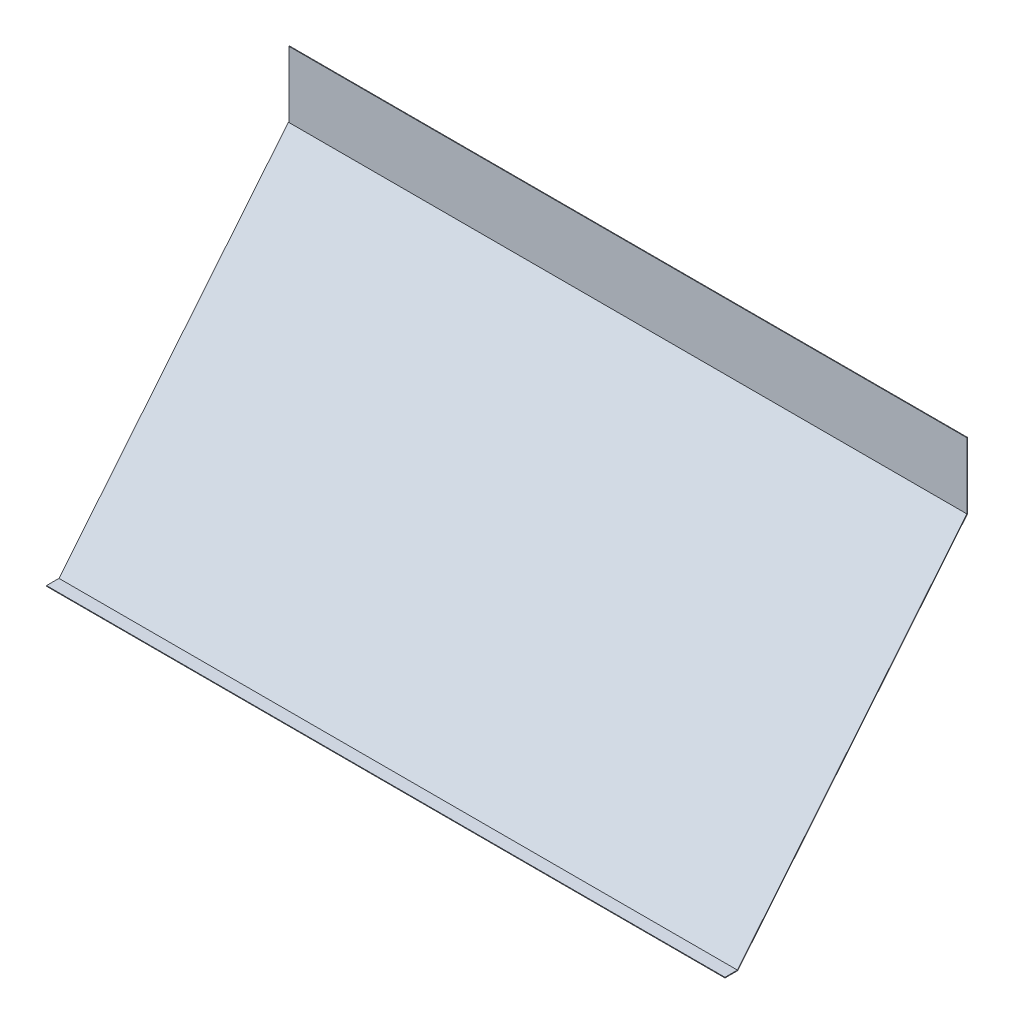
SolidWorks part; units mm, degrees
ref_plane "Front Plane" through (0, 0, 0) normal (0, 0, 1) x (1, 0, 0)
ref_plane "Top Plane" through (0, 0, 0) normal (0, 1, 0) x (1, 0, 0)
ref_plane "Right Plane" through (0, 0, 0) normal (1, 0, 0) x (0, 0, -1)
sketch "Sketch1" plane through (0, 0, 0) normal (0, 1, 0) x (1, 0, 0)
  line L1 (-545, 10) -> (545, 10)
  line L2 (-545, 10) -> (-545, -10)
  line L3 (-545, -10) -> (545, -10)
  line L4 (545, 10) -> (545, -10)
  line L5 (-545, 10) -> (545, -10) construction
  line L6 (-545, -10) -> (545, 10) construction
  point P0 (0, 0)
  dimension "D1" = 1090
  dimension "D2" = 20
extrude "Boss-Extrude1" add sketch "Sketch1" along normal blind 1
sketch "Sketch4" plane through (-545, 0, 0) normal (-1, 0, 0) x (0, 0, 1)
  line L0 (-10, 0) -> (-10, 1)
  line L1 (-10, 1) -> (-10.7738, 0.3666)
  arc A0 (-10.7738, 0.3666) -> (-10, 0) centre (-10, 1) ccw
  line M6 (-10, 1) -> (-10, 0)
  dimension "D1" = 1
  dimension "D2" = 50.7
extrude "Boss-Extrude4" add sketch "Sketch4" along direction (-1, 0, 0) on the side against the normal blind 1090 contours L1 A0 M6
sketch "Sketch5" plane through (0, 5.5002, -4.5018) normal (0, 0.7738, -0.6334) x (1, 0, 0)
  line L1 (-545, 7.105) -> (545, 7.105)
  line L2 (-545, 7.105) -> (-545, 8.105)
  line L3 (-545, 8.105) -> (545, 8.105)
  line L4 (545, 7.105) -> (545, 8.105)
extrude "Boss-Extrude5" add sketch "Sketch5" along normal blind 582
sketch "Sketch6" plane through (545, 0, 0) normal (1, 0, 0) x (0, 0, -1)
  line L0 (378.6277, 451.375) -> (379.6277, 451.375)
  line L1 (378.6277, 451.375) -> (379.4015, 450.7416) construction
  line L2 (379.4015, 450.7416) -> (378.6277, 451.375)
  arc A0 (379.6277, 451.375) -> (379.4015, 450.7416) centre (378.6277, 451.375) cw
  dimension "D1" = 1
  dimension "D2" = 39.3
extrude "Boss-Extrude6" add sketch "Sketch6" against normal blind 1090
sketch "Sketch7" plane through (0, 451.375, 0) normal (0, 1, 0) x (1, 0, 0)
  line L0 (-545, 378.6277) -> (545, 378.6277) construction
  line L1 (545, 378.6277) -> (-544, 378.6277)
  line L2 (545, 378.6277) -> (545, 379.6277)
  line L3 (545, 379.6277) -> (-544, 379.6277)
  line L4 (-544, 378.6277) -> (-544, 379.6277)
  line L5 (-545, 379.6277) -> (545, 379.6277) construction
extrude "Boss-Extrude7" add sketch "Sketch7" along normal blind 106
